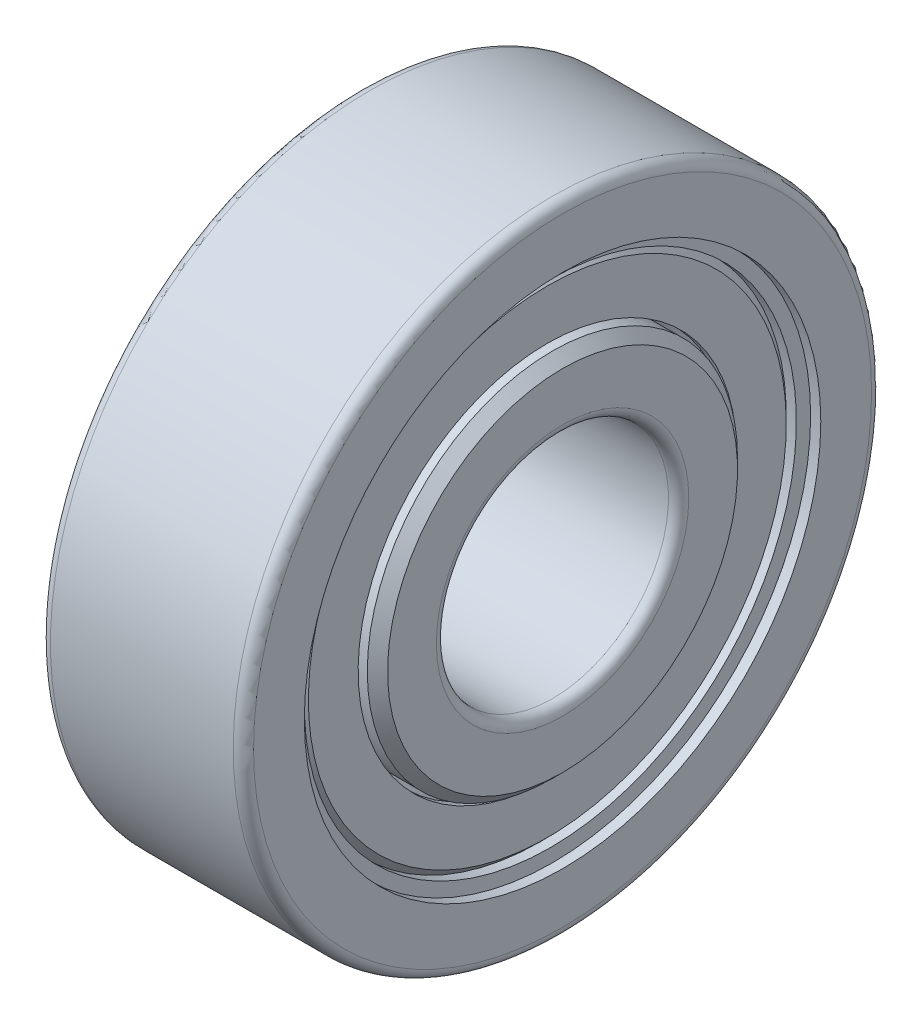
SolidWorks part; units mm, degrees
ref_plane "前视基准面" through (0, 0, 0) normal (0, 0, 1) x (1, 0, 0)
ref_plane "上视基准面" through (0, 0, 0) normal (0, 1, 0) x (1, 0, 0)
ref_plane "右视基准面" through (0, 0, 0) normal (1, 0, 0) x (0, 0, -1)
sketch "草图1" plane through (0, 0, 0) normal (0, 0, 1) x (1, 0, 0)
  line L0 (0, 7.36) -> (0, 0) construction
  line L1 (0, 0) -> (0, 0.6378) construction
  line L2 (-3.5, 4) -> (-3.5, 6.38)
  line L3 (-3.5, 8.9) -> (-3.5, 11)
  line L4 (-3.15, 8.9) -> (-3.5, 8.9)
  line L5 (-3.08, 9.0212) -> (-3.15, 8.9)
  line L6 (-3.08, 8.48) -> (-3.08, 9.0212)
  line L7 (-2.73, 8.48) -> (-3.08, 8.48)
  line L8 (-2.975, 8.235) -> (-2.73, 8.48)
  line L9 (-2.975, 6.52) -> (-2.975, 8.235)
  line L10 (-2.73, 6.52) -> (-2.975, 6.52)
  line L11 (-2.73, 8.2) -> (-2.73, 6.52)
  line L12 (-2.45, 8.48) -> (-2.73, 8.2)
  line L13 (-0.84, 8.48) -> (-2.45, 8.48)
  line L14 (-3.5, 6.38) -> (-0.9998, 6.38)
  line L15 (0, 0) -> (-7.667, 0) construction
  line L61 (3.5, 6.38) -> (0.9998, 6.38)
  line L62 (0.84, 8.48) -> (2.45, 8.48)
  line L63 (2.45, 8.48) -> (2.73, 8.2)
  line L64 (2.73, 8.2) -> (2.73, 6.52)
  line L65 (2.73, 6.52) -> (2.975, 6.52)
  line L66 (2.975, 6.52) -> (2.975, 8.235)
  line L67 (2.975, 8.235) -> (2.73, 8.48)
  line L68 (2.73, 8.48) -> (3.08, 8.48)
  line L69 (3.08, 8.48) -> (3.08, 9.0212)
  line L70 (3.08, 9.0212) -> (3.15, 8.9)
  line L71 (3.15, 8.9) -> (3.5, 8.9)
  line L72 (3.5, 8.9) -> (3.5, 11)
  line L73 (3.5, 11) -> (-3.5, 11)
  line L88 (-3.5, 4) -> (3.5, 4)
  line L89 (3.5, 4) -> (3.5, 6.38)
  arc A0 (-0.9998, 6.38) -> (-0.84, 8.48) centre (0, 7.36) cw
  arc A12 (0.9998, 6.38) -> (0.84, 8.48) centre (0, 7.36) ccw
  dimension "D4" = 2.8
  dimension "D1" = 7
  dimension "D2" = 8
  dimension "D3" = 22
  dimension "D5" = 2.38
  dimension "D6" = 3.36
  dimension "D7" = 2.1
  dimension "D8" = 2.52
  dimension "D9" = 6.3
  dimension "D10" = 30
  dimension "D11" = 2.52
  dimension "D12" = 45
  dimension "D13" = 6.16
  dimension "D14" = 5.95
  dimension "D15" = 5.46
  dimension "D16" = 4.9
revolve "旋转1" add sketch "草图1" angle 360 about L15
fillet "圆角1" radius 0.35 4 edges at (3.5, 4, 0) (-3.5, 4, 0) (-3.5, 11, 0) (3.5, 11, 0)
chamfer "倒角1" distance 0.35 angle 45 2 edges at (3.5, 6.38, 0) (-3.5, 6.38, 0)
